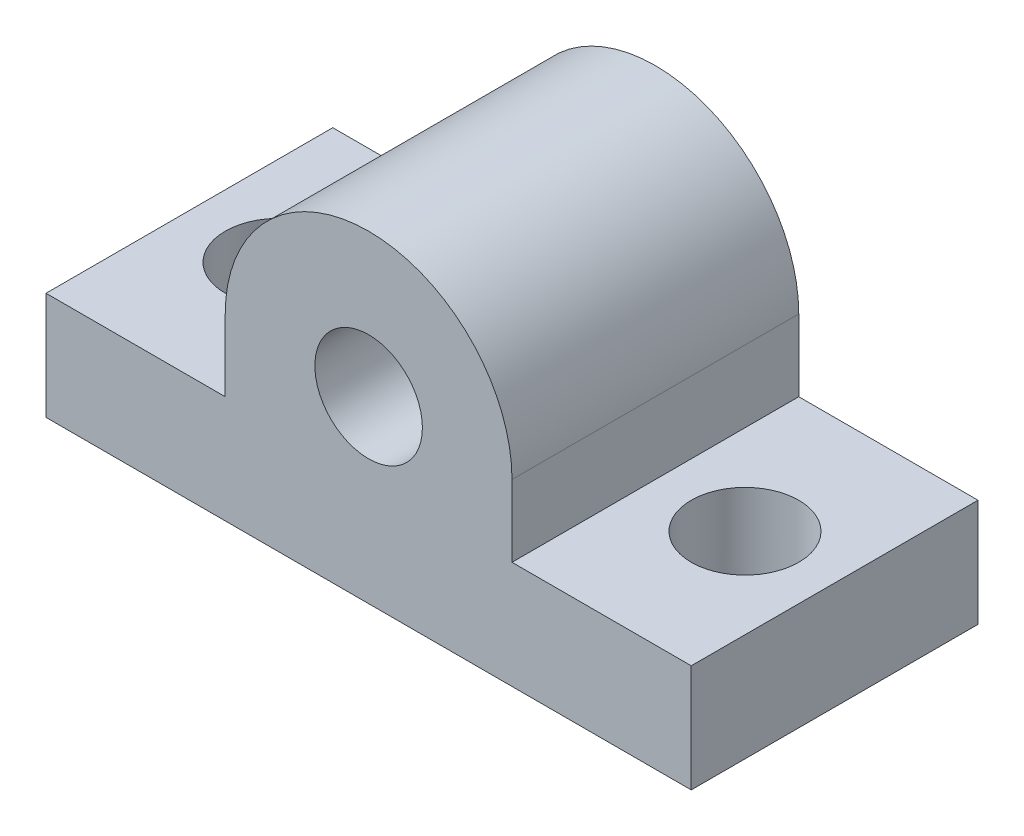
SolidWorks part; units mm, degrees
ref_plane "Front Plane" through (0, 0, 0) normal (0, 0, 1) x (1, 0, 0)
ref_plane "Top Plane" through (0, 0, 0) normal (0, 1, 0) x (1, 0, 0)
ref_plane "Right Plane" through (0, 0, 0) normal (1, 0, 0) x (0, 0, -1)
sketch "Sketch1" plane through (0, 0, 0) normal (0, 0, 1) x (1, 0, 0)
  line L1 (0, 0) -> (8, 0)
  line L2 (0, 0) -> (0, 5)
  line L3 (0, 5) -> (8, 5)
  line L4 (8, 0) -> (8, 5)
  circle A0 centre (4, 5) radius 4
  circle A1 centre (4, 5) radius 1.5
  dimension "D3" = 3
  dimension "D1" = 5
  dimension "D2" = 8
extrude "Boss-Extrude1" add sketch "Sketch1" along normal blind 8 contours A1 L3 A0 | A1 L3 A0 | A0 L2 L1 L4
sketch "Sketch2" plane through (8, 0, 0) normal (1, 0, 0) x (0, 0, -1)
  line L0 (-8, 0) -> (-8, 5) construction
  line L1 (0, 0) -> (-8, 0)
  line L2 (0, 0) -> (0, 3)
  line L3 (0, 3) -> (-8, 3)
  line L4 (-8, 0) -> (-8, 3)
  dimension "D1" = 3
extrude "Boss-Extrude2" add sketch "Sketch2" along normal blind 5
sketch "Sketch3" plane through (0, 3, 0) normal (0, 1, 0) x (1, 0, 0)
  line L0 (8, 0) -> (8, -8) construction
  line L2 (13, 0) -> (8, 0) construction
  circle A0 centre (10.5, -4) radius 1.5
  dimension "D1" = 3
  dimension "D2" = 2.5
  dimension "D3" = 4
extrude "Cut-Extrude1" cut sketch "Sketch3" against normal up to next
sketch "Sketch4" plane through (0, 0, 0) normal (-1, 0, 0) x (0, 0, 1)
  line L5 (8, 0) -> (8, 5) construction
  line L6 (0, 0) -> (8, 0)
  line L7 (0, 0) -> (0, 3)
  line L8 (0, 3) -> (8, 3)
  line L9 (8, 0) -> (8, 3)
  dimension "D1" = 3
extrude "Boss-Extrude3" add sketch "Sketch4" along normal blind 5
sketch "Sketch5" plane through (0, 3, 0) normal (0, 1, 0) x (1, 0, 0)
  line L0 (0, -8) -> (0, 0) construction
  line L1 (-5, 0) -> (0, 0) construction
  circle A0 centre (-2.5, -4) radius 1.5
  dimension "D1" = 3
  dimension "D2" = 2.5
  dimension "D3" = 4
extrude "Cut-Extrude2" cut sketch "Sketch5" against normal up to next
